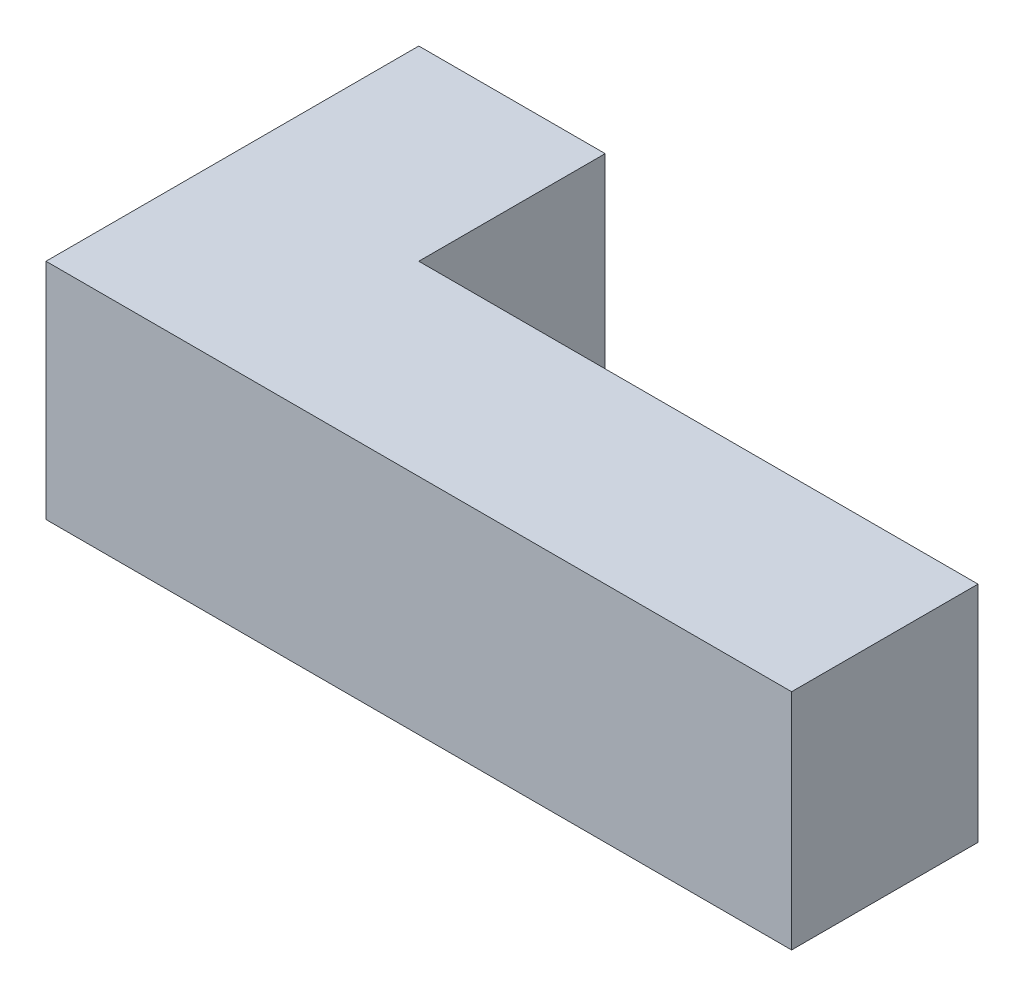
SolidWorks part; units mm, degrees
ref_plane "Přední rovina" through (0, 0, 0) normal (0, 0, 1) x (1, 0, 0)
ref_plane "Horní rovina" through (0, 0, 0) normal (0, 1, 0) x (1, 0, 0)
ref_plane "Pravá rovina" through (0, 0, 0) normal (1, 0, 0) x (0, 0, -1)
sketch "Skica1" plane through (0, 0, 0) normal (0, 1, 0) x (1, 0, 0)
  line L1 (0, 0) -> (100, 0)
  line L6 (0, 0) -> (0, 50)
  line L7 (0, 0) -> (100, 0)
  line L15 (0, 50) -> (25, 50)
  line L16 (25, 50) -> (25, 25)
  line L17 (25, 25) -> (100, 25)
  line L18 (100, 25) -> (100, 0)
  line L19 (0, 0) -> (0, 50)
  point P0 (100, 11.5549)
  dimension "D1" = 100
  dimension "D2" = 50
  dimension "D5" = 25
  dimension "D6" = 75
extrude "Přidat vysunutím1" add sketch "Skica1" along normal blind 30 contours L18 L17 L16 L15 L6 L1
